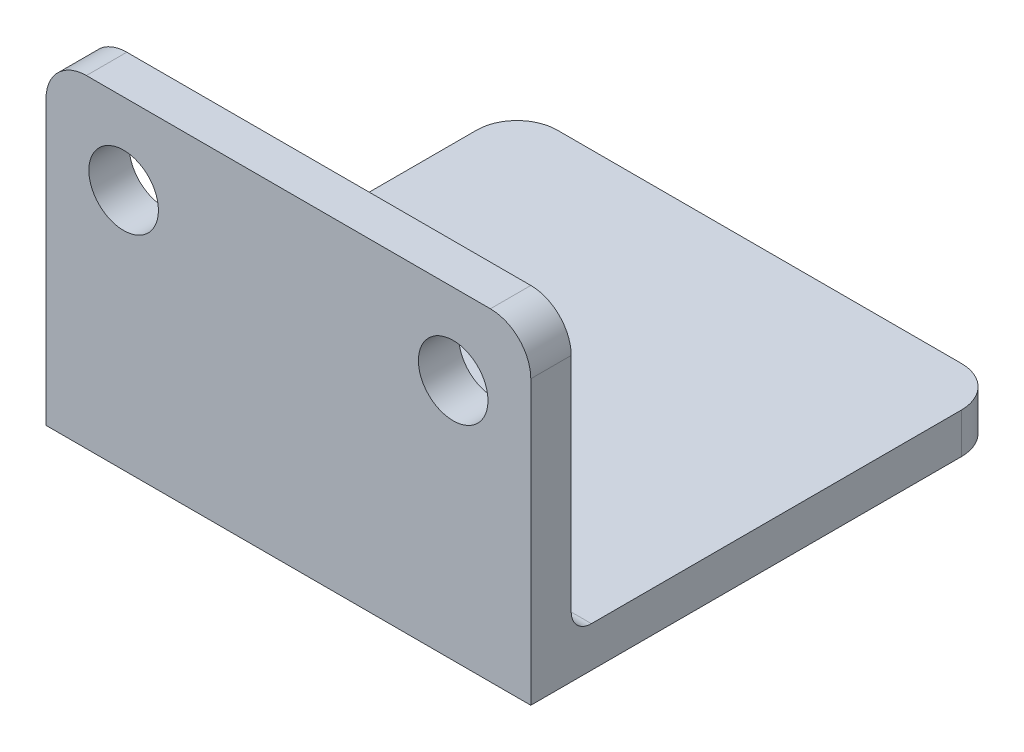
SolidWorks part; units mm, degrees
ref_plane "Front Plane" through (0, 0, 0) normal (0, 0, 1) x (1, 0, 0)
ref_plane "Top Plane" through (0, 0, 0) normal (0, 1, 0) x (1, 0, 0)
ref_plane "Right Plane" through (0, 0, 0) normal (1, 0, 0) x (0, 0, -1)
sketch "Sketch1" plane through (0, 0, 0) normal (1, 0, 0) x (0, 0, -1)
  line L0 (74.0265, 0) -> (0, 0)
  line L1 (0, 0) -> (0, 50.8)
  dimension "D1" = 50.8
extrude "Extrude-Thin1" add sketch "Sketch1" along normal blind 76.2 thin
fillet "Fillet1" radius 6.35 4 edges at (0, 3.175, -74.0265) (76.2, 3.175, -74.0265) (0, 50.8, -3.175) (76.2, 50.8, -3.175)
sketch "Sketch3" plane through (0, 0, 0) normal (0, 0, 1) x (1, 0, 0)
  line L0 (38.1, 50.8) -> (38.1, 14.1176) construction
  line L1 (69.85, 50.8) -> (6.35, 50.8) construction
  circle A0 centre (12.2019, 38.1) radius 5.4702
  circle A1 centre (63.9981, 38.1) radius 5.4702
  dimension "D2" = 10.9405
  dimension "D1" = 38.1
extrude "Cut-Extrude2" cut sketch "Sketch3" against normal blind 76.2
fillet "Fillet2" radius 3.175 1 edges at (38.1, 6.35, -6.35)
